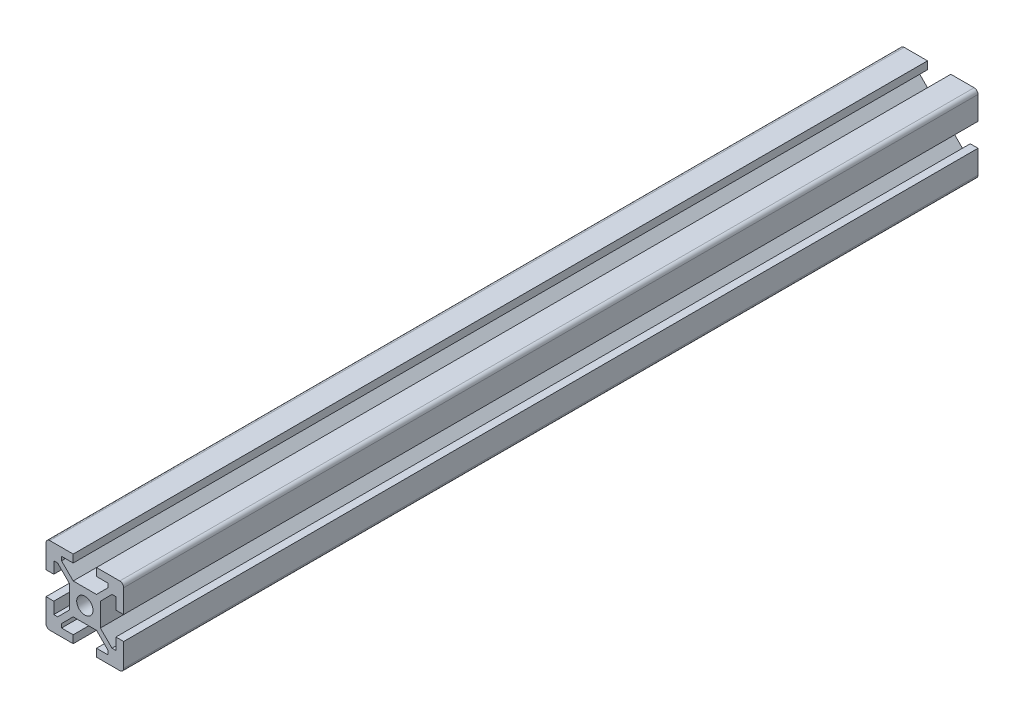
SolidWorks part; units mm, degrees
material "6063-T5"
ref_plane "Front Plane" through (0, 0, 0) normal (0, 0, 1) x (1, 0, 0)
ref_plane "Top Plane" through (0, 0, 0) normal (0, 1, 0) x (1, 0, 0)
ref_plane "Right Plane" through (0, 0, 0) normal (1, 0, 0) x (0, 0, -1)
ref_plane "Plane1" through (0, 0, 0) normal (0, 0, -1) x (-1, 0, 0)
sketch "Sketch1" plane through (0, 0, 0) normal (0, 0, -1) x (-1, 0, 0)
  line L0 (6, -8) -> (3, -8)
  line L1 (3, -8) -> (3, -10)
  line L2 (3, -10) -> (9, -10)
  line L3 (10, -9) -> (10, -3)
  line L4 (10, -3) -> (8, -3)
  line L5 (8, -3) -> (8, -6)
  line L6 (8, -6) -> (7, -6)
  line L7 (7, -6) -> (4, -3)
  line L8 (4, -3) -> (4, 3)
  line L9 (4, 3) -> (7, 6)
  line L10 (7, 6) -> (8, 6)
  line L11 (8, 6) -> (8, 3)
  line L12 (8, 3) -> (10, 3)
  line L13 (10, 3) -> (10, 9)
  line L14 (9, 10) -> (3, 10)
  line L15 (3, 10) -> (3, 8)
  line L16 (3, 8) -> (6, 8)
  line L17 (6, 8) -> (6, 7)
  line L18 (6, 7) -> (3, 4)
  line L19 (3, 4) -> (-3, 4)
  line L20 (-3, 4) -> (-6, 7)
  line L21 (-6, 7) -> (-6, 8)
  line L22 (-6, 8) -> (-3, 8)
  line L23 (-3, 8) -> (-3, 10)
  line L24 (-3, 10) -> (-9, 10)
  line L25 (-10, 9) -> (-10, 3)
  line L26 (-10, 3) -> (-8, 3)
  line L27 (-8, 3) -> (-8, 6)
  line L28 (-8, 6) -> (-7, 6)
  line L29 (-7, 6) -> (-4, 3)
  line L30 (-4, 3) -> (-4, -3)
  line L31 (-4, -3) -> (-7, -6)
  line L32 (-7, -6) -> (-8, -6)
  line L33 (-8, -6) -> (-8, -3)
  line L34 (-8, -3) -> (-10, -3)
  line L35 (-10, -3) -> (-10, -9)
  line L36 (-9, -10) -> (-3, -10)
  line L37 (-3, -10) -> (-3, -8)
  line L38 (-3, -8) -> (-6, -8)
  line L39 (-6, -8) -> (-6, -7)
  line L40 (-6, -7) -> (-3, -4)
  line L41 (-3, -4) -> (3, -4)
  line L42 (3, -4) -> (6, -7)
  line L43 (6, -7) -> (6, -8)
  line L44 (0, 4) -> (0, 0) construction
  line L45 (0, 0) -> (-4, 0) construction
  line L46 (0, 0) -> (4, 0) construction
  line L47 (0, 0) -> (0, -4) construction
  circle A0 centre (0, 0) radius 2.1
  arc A1 (9, -10) -> (10, -9) centre (9, -9) ccw
  arc A2 (10, 9) -> (9, 10) centre (9, 9) ccw
  arc A3 (-9, 10) -> (-10, 9) centre (-9, 9) ccw
  arc A4 (-10, -9) -> (-9, -10) centre (-9, -9) ccw
  dimension "D6" = 1
  dimension "D10" = 4.2
  dimension "D1" = 10
  dimension "D2" = 10
  dimension "D3" = 10
  dimension "D4" = 10
  dimension "D5" = 8
  dimension "D7" = 2
  dimension "D8" = 7
  dimension "D9" = 8
  dimension "D11" = 1
  dimension "D12" = 1
  dimension "D13" = 2
  dimension "D14" = 3
  dimension "D15" = 2
  dimension "D16" = 1
  dimension "D17" = 1
  dimension "D18" = 4.2426
  dimension "D19" = 6
  dimension "D20" = 7
extrude "Boss-Extrude1" add sketch "Sketch1" against normal blind 220
ref_plane "Plane2" through (0, 0, 0) normal (1, 0, 0) x (0, 0, -1)
